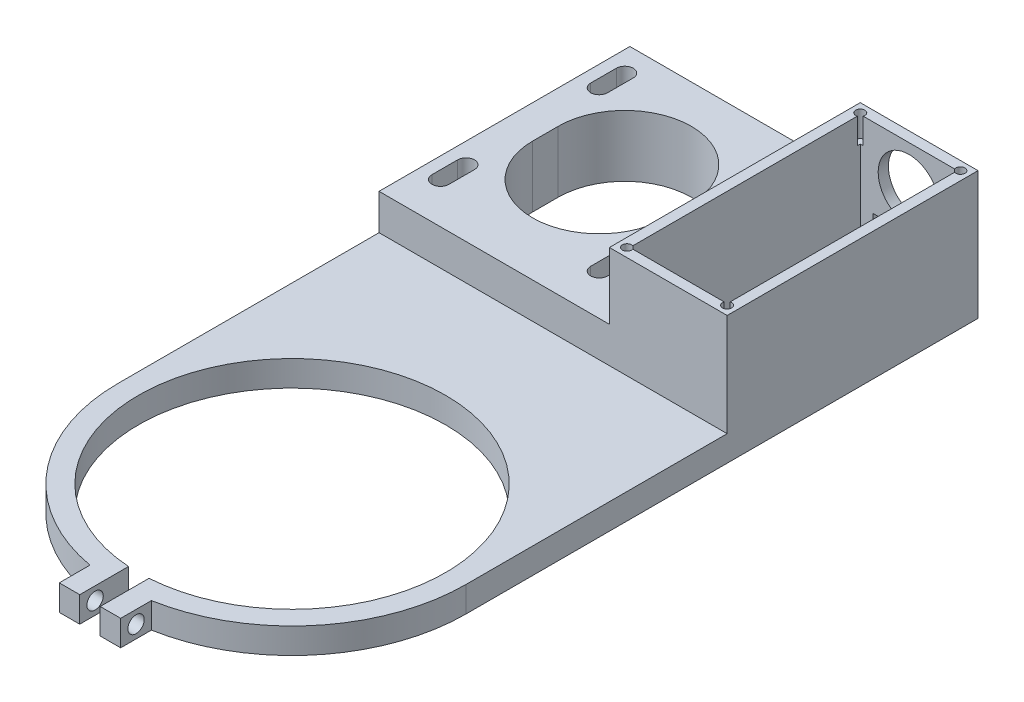
SolidWorks part; units mm, degrees
ref_plane "前视基准面" through (0, 0, 0) normal (0, 0, 1) x (1, 0, 0)
ref_plane "上视基准面" through (0, 0, 0) normal (0, 1, 0) x (1, 0, 0)
ref_plane "右视基准面" through (0, 0, 0) normal (1, 0, 0) x (0, 0, -1)
sketch "草图2" plane through (0, 0, 0) normal (0, 1, 0) x (1, 0, 0)
  line L0 (-2, -29.9333) -> (-2, -39.4664)
  line L4 (2, -29.9333) -> (2, -39.4664)
  line L7 (2, -39.4664) -> (6, -39.4664)
  line L8 (6, -39.4664) -> (6, -33.4664)
  line L9 (-2, -39.4664) -> (-6, -39.4664)
  line L10 (-6, -39.4664) -> (-6, -33.4664)
  line L11 (-34, 0) -> (-34, 100)
  line L12 (-34, 100) -> (11, 100)
  line L13 (34, 51) -> (34, 0)
  line L14 (0, 18.6389) -> (0, -49.9777) construction
  line L15 (-30, 64) -> (-30, 59) construction
  line L16 (-28.35, 64) -> (-28.35, 59)
  line L17 (-31.65, 64) -> (-31.65, 59)
  line L18 (1, 64) -> (1, 59) construction
  line L19 (2.65, 64) -> (2.65, 59)
  line L20 (-0.65, 64) -> (-0.65, 59)
  line L21 (-14.5, 79.5) -> (-14.5, 74.5) construction
  line L22 (-1.5, 79.5) -> (-1.5, 74.5)
  line L23 (-27.5, 79.5) -> (-27.5, 74.5)
  line L24 (-30, 95) -> (-30, 90) construction
  line L25 (-28.35, 95) -> (-28.35, 90)
  line L26 (-31.65, 95) -> (-31.65, 90)
  line L27 (1, 95) -> (1, 90) construction
  line L28 (2.65, 95) -> (2.65, 90)
  line L29 (-0.65, 95) -> (-0.65, 90)
  line L30 (34, 51) -> (11, 51)
  line L31 (11, 51) -> (11, 100)
  arc A3 (-2, -29.9333) -> (2, -29.9333) centre (0, 0) cw
  arc A4 (-34, 0) -> (-6, -33.4664) centre (0, 0) ccw
  arc A5 (6, -33.4664) -> (34, 0) centre (0, 0) ccw
  arc A6 (-28.35, 64) -> (-31.65, 64) centre (-30, 64) ccw
  arc A7 (-31.65, 59) -> (-28.35, 59) centre (-30, 59) ccw
  arc A8 (2.65, 64) -> (-0.65, 64) centre (1, 64) ccw
  arc A9 (-0.65, 59) -> (2.65, 59) centre (1, 59) ccw
  arc A10 (-1.5, 79.5) -> (-27.5, 79.5) centre (-14.5, 79.5) ccw
  arc A11 (-27.5, 74.5) -> (-1.5, 74.5) centre (-14.5, 74.5) ccw
  arc A12 (-28.35, 95) -> (-31.65, 95) centre (-30, 95) ccw
  arc A13 (-31.65, 90) -> (-28.35, 90) centre (-30, 90) ccw
  arc A14 (2.65, 95) -> (-0.65, 95) centre (1, 95) ccw
  arc A15 (-0.65, 90) -> (2.65, 90) centre (1, 90) ccw
  point P8 (-30, 61.5)
  point P23 (1, 61.5)
  point P30 (-14.5, 77)
  point P37 (-30, 92.5)
  point P46 (1, 92.5)
  dimension "D1" = 30
  dimension "D2" = 34
  dimension "D3" = 4
  dimension "D4" = 4
  dimension "D5" = 6
  dimension "D6" = 100
  dimension "D7" = 15.5
  dimension "D8" = 31
  dimension "D9" = 1.65
  dimension "D10" = 31
  dimension "D11" = 5
  dimension "D12" = 4
  dimension "D13" = 5
  dimension "D14" = 5
  dimension "D15" = 13
  dimension "D16" = 49
  dimension "D17" = 23
extrude "凸台-拉伸1" add sketch "草图2" along normal blind 5 contours L8 A5 L13 L30 L31 L12 L11 A4 L10 L9 L0 A3 L4 L7 A15 L29 A14 L28 A13 L26 A12 L25 A11 L23 A10 L22 A9 L20 A8 L19 A7 L17 A6 L16
sketch "草图4" plane through (0, 0, 0) normal (1, 0, 0) x (0, 0, -1)
  line L0 (-36.4664, 5) -> (-36.4664, 0) construction
  line L1 (-33.4664, 2.5) -> (-39.4664, 2.5) construction
  line L4 (-39.4664, 0) -> (-33.4664, 0)
  line L5 (-33.4664, 0) -> (-33.4664, 5)
  line L6 (-33.4664, 5) -> (-39.4664, 5)
  line L7 (-39.4664, 5) -> (-39.4664, 0)
  line L8 (-39.4664, 0) -> (-33.4664, 0) construction
  line L9 (-33.4664, 0) -> (-33.4664, 5) construction
  line L10 (-33.4664, 5) -> (-39.4664, 5) construction
  line L11 (-39.4664, 5) -> (-39.4664, 0) construction
  circle A0 centre (-36.4664, 2.5) radius 1.6
  point P11 (-36.4664, 2.5)
  dimension "D2" = 3.2
  dimension "D1" = 0
extrude "切除-拉伸1" cut sketch "草图4" against normal mid plane 20
sketch "草图5" plane through (0, 0, 0) normal (0, 1, 0) x (1, 0, 0)
  line L0 (11, 100) -> (34, 100)
  line L1 (34, 100) -> (34, 51)
  line L11 (6, -39.4664) -> (6, -33.4664)
  line L12 (34, 0) -> (34, 51)
  line L13 (34, 51) -> (11, 51)
  line L14 (11, 51) -> (11, 100)
  line L15 (11, 100) -> (-34, 100)
  line L16 (-34, 100) -> (-34, 0)
  line L17 (-6, -33.4664) -> (-6, -39.4664)
  line L18 (-6, -39.4664) -> (-2, -39.4664)
  line L19 (-2, -39.4664) -> (-2, -29.9333)
  line L20 (2, -29.9333) -> (2, -39.4664)
  line L21 (2, -39.4664) -> (6, -39.4664)
  line L24 (34, 51) -> (11, 51)
  line L25 (11, 51) -> (11, 100)
  arc A3 (6, -33.4664) -> (34, 0) centre (0, 0) ccw
  arc A4 (-34, 0) -> (-6, -33.4664) centre (0, 0) ccw
  arc A5 (2, -29.9333) -> (-2, -29.9333) centre (0, 0) ccw
  dimension "D1" = 0
extrude "凸台-拉伸2" add sketch "草图5" along normal blind 25 separate body
shell "抽壳1" thickness 2
ref_plane "基准面1" through (0, 0, -100) normal (0, 0, -1) x (-1, 0, 0)
sketch "草图6" plane through (0, 0, -100) normal (0, 0, -1) x (-1, 0, 0)
  line L1 (-29.5, 2.5) -> (-15.5, 2.5)
  line L2 (-29.5, 2.5) -> (-29.5, 9.5)
  line L3 (-29.5, 9.5) -> (-15.5, 9.5)
  line L4 (-34, 0) -> (-11, 0)
  line L5 (-11, 0) -> (-11, 25)
  line L6 (-11, 25) -> (-34, 25)
  line L7 (-34, 25) -> (-34, 0)
  line L8 (-34, 0) -> (-11, 0) construction
  line L9 (-11, 0) -> (-11, 25) construction
  line L10 (-11, 25) -> (-34, 25) construction
  line L11 (-34, 25) -> (-34, 0) construction
  line L12 (-15.5, 2.5) -> (-15.5, 9.5)
  line L13 (-29.5, 2.5) -> (-15.5, 9.5) construction
  line L14 (-29.5, 9.5) -> (-15.5, 2.5) construction
  circle A0 centre (-22.5, 17) radius 6
  point P6 (-22.5, 6)
  point P12 (-22.5, 0)
  dimension "D5" = 12
  dimension "D2" = 14
  dimension "D3" = 7
  dimension "D4" = 2.5
  dimension "D6" = 8
  dimension "D1" = 0
extrude "切除-拉伸2" cut sketch "草图6" against normal up to next (2 mm away)
ref_plane "基准面2" through (0, 25, 0) normal (0, 1, 0) x (1, 0, 0)
sketch "草图7" plane through (0, 25, 0) normal (0, 1, 0) x (1, 0, 0)
  line L0 (11, 100) -> (13, 98) construction
  line L1 (32, 98) -> (34, 100) construction
  line L2 (13, 53) -> (11, 51) construction
  line L3 (32, 53) -> (34, 51) construction
  line L4 (13, 53) -> (32, 53)
  line L5 (13, 98) -> (13, 53)
  line L6 (32, 98) -> (13, 98)
  line L7 (32, 53) -> (32, 98)
  line L8 (13, 53) -> (32, 53) construction
  line L9 (13, 98) -> (13, 53) construction
  line L10 (32, 98) -> (13, 98) construction
  line L11 (32, 53) -> (32, 98) construction
  line L12 (11, 51) -> (34, 51)
  line L13 (34, 51) -> (34, 100)
  line L14 (34, 100) -> (11, 100)
  line L15 (11, 100) -> (11, 51)
  line L16 (11, 51) -> (34, 51) construction
  line L17 (34, 51) -> (34, 100) construction
  line L18 (34, 100) -> (11, 100) construction
  line L19 (11, 100) -> (11, 51) construction
  circle A0 centre (12.7172, 52.7172) radius 0.9
  circle A1 centre (32.2828, 52.7172) radius 0.9
  circle A3 centre (32.2828, 98.2828) radius 0.9
  circle A4 centre (12.7172, 98.2828) radius 0.9
  dimension "D3" = 1.8
  dimension "D4" = 0.4
  dimension "D1" = 0
  dimension "D2" = 0
extrude "切除-拉伸3" cut sketch "草图7" against normal blind 5
ref_plane "基准面3" through (0, 2, 0) normal (0, 1, 0) x (1, 0, 0)
sketch "草图10" plane through (0, 2, 0) normal (0, 1, 0) x (1, 0, 0)
  line L0 (22.5, 98) -> (22.5, 53) construction
  line L1 (13, 75.5) -> (32, 75.5) construction
  line L4 (13, 53) -> (32, 53)
  line L5 (32, 53) -> (32, 98)
  line L6 (32, 98) -> (13, 98)
  line L7 (13, 98) -> (13, 53)
  line L8 (13, 53) -> (32, 53) construction
  line L9 (32, 53) -> (32, 98) construction
  line L10 (32, 98) -> (13, 98) construction
  line L11 (13, 98) -> (13, 53) construction
  circle A0 centre (15, 95.75) radius 0.9
  circle A1 centre (30, 95.75) radius 0.9
  circle A2 centre (30, 55.25) radius 0.9
  circle A3 centre (15, 55.25) radius 0.9
  dimension "D2" = 1.8
  dimension "D3" = 15
  dimension "D4" = 40.5
  dimension "D1" = 0
extrude "切除-拉伸4" cut sketch "草图10" against normal blind 10
ref_plane "基准面4" through (0, 5, 0) normal (0, 1, 0) x (1, 0, 0)
sketch "草图11" plane through (0, 5, 0) normal (0, 1, 0) x (1, 0, 0)
  line L0 (11, 51) -> (-34, 51)
  line L1 (-34, 0) -> (-34, 100) construction
  line L2 (-0.65, 95) -> (-0.65, 90)
  line L3 (2.65, 90) -> (2.65, 95)
  line L4 (-0.65, 95) -> (-0.65, 90)
  line L5 (2.65, 90) -> (2.65, 95)
  line L6 (-31.65, 95) -> (-31.65, 90)
  line L7 (-28.35, 90) -> (-28.35, 95)
  line L8 (-31.65, 95) -> (-31.65, 90)
  line L9 (-28.35, 90) -> (-28.35, 95)
  line L10 (-27.5, 79.5) -> (-27.5, 74.5)
  line L11 (6, -39.4664) -> (6, -33.4664)
  line L12 (34, 0) -> (34, 51)
  line L13 (34, 51) -> (11, 51)
  line L14 (11, 51) -> (11, 100)
  line L15 (11, 100) -> (-34, 100)
  line L16 (-34, 100) -> (-34, 0)
  line L17 (-6, -33.4664) -> (-6, -39.4664)
  line L18 (-6, -39.4664) -> (-2, -39.4664)
  line L19 (-2, -39.4664) -> (-2, -29.9333)
  line L20 (2, -29.9333) -> (2, -39.4664)
  line L21 (2, -39.4664) -> (6, -39.4664)
  line L25 (11, 51) -> (11, 100)
  line L26 (11, 100) -> (-34, 100)
  line L33 (-1.5, 74.5) -> (-1.5, 79.5)
  line L34 (-27.5, 79.5) -> (-27.5, 74.5)
  line L35 (-1.5, 74.5) -> (-1.5, 79.5)
  line L36 (-0.65, 64) -> (-0.65, 59)
  line L37 (2.65, 59) -> (2.65, 64)
  line L38 (-0.65, 64) -> (-0.65, 59)
  line L39 (2.65, 59) -> (2.65, 64)
  line L40 (-31.65, 64) -> (-31.65, 59)
  line L41 (-28.35, 59) -> (-28.35, 64)
  line L42 (-31.65, 64) -> (-31.65, 59)
  line L43 (-28.35, 59) -> (-28.35, 64)
  line L44 (-34, 51) -> (-34, 100)
  arc A2 (-0.65, 90) -> (2.65, 90) centre (1, 90) ccw
  arc A3 (6, -33.4664) -> (34, 0) centre (0, 0) ccw
  arc A4 (-34, 0) -> (-6, -33.4664) centre (0, 0) ccw
  arc A5 (2, -29.9333) -> (-2, -29.9333) centre (0, 0) ccw
  arc A9 (2.65, 95) -> (-0.65, 95) centre (1, 95) ccw
  arc A10 (-0.65, 90) -> (2.65, 90) centre (1, 90) ccw
  arc A11 (2.65, 95) -> (-0.65, 95) centre (1, 95) ccw
  arc A12 (-31.65, 90) -> (-28.35, 90) centre (-30, 90) ccw
  arc A13 (-28.35, 95) -> (-31.65, 95) centre (-30, 95) ccw
  arc A14 (-31.65, 90) -> (-28.35, 90) centre (-30, 90) ccw
  arc A15 (-28.35, 95) -> (-31.65, 95) centre (-30, 95) ccw
  arc A16 (-27.5, 74.5) -> (-1.5, 74.5) centre (-14.5, 74.5) ccw
  arc A17 (-1.5, 79.5) -> (-27.5, 79.5) centre (-14.5, 79.5) ccw
  arc A18 (-27.5, 74.5) -> (-1.5, 74.5) centre (-14.5, 74.5) ccw
  arc A19 (-1.5, 79.5) -> (-27.5, 79.5) centre (-14.5, 79.5) ccw
  arc A20 (-0.65, 59) -> (2.65, 59) centre (1, 59) ccw
  arc A21 (2.65, 64) -> (-0.65, 64) centre (1, 64) ccw
  arc A22 (-0.65, 59) -> (2.65, 59) centre (1, 59) ccw
  arc A23 (2.65, 64) -> (-0.65, 64) centre (1, 64) ccw
  arc A24 (-31.65, 59) -> (-28.35, 59) centre (-30, 59) ccw
  arc A25 (-28.35, 64) -> (-31.65, 64) centre (-30, 64) ccw
  arc A26 (-31.65, 59) -> (-28.35, 59) centre (-30, 59) ccw
  arc A27 (-28.35, 64) -> (-31.65, 64) centre (-30, 64) ccw
  dimension "D1" = 0
  dimension "D2" = 0
  dimension "D3" = 0
  dimension "D4" = 0
  dimension "D5" = 0
  dimension "D6" = 0
extrude "凸台-拉伸3" add sketch "草图11" along normal blind 7
